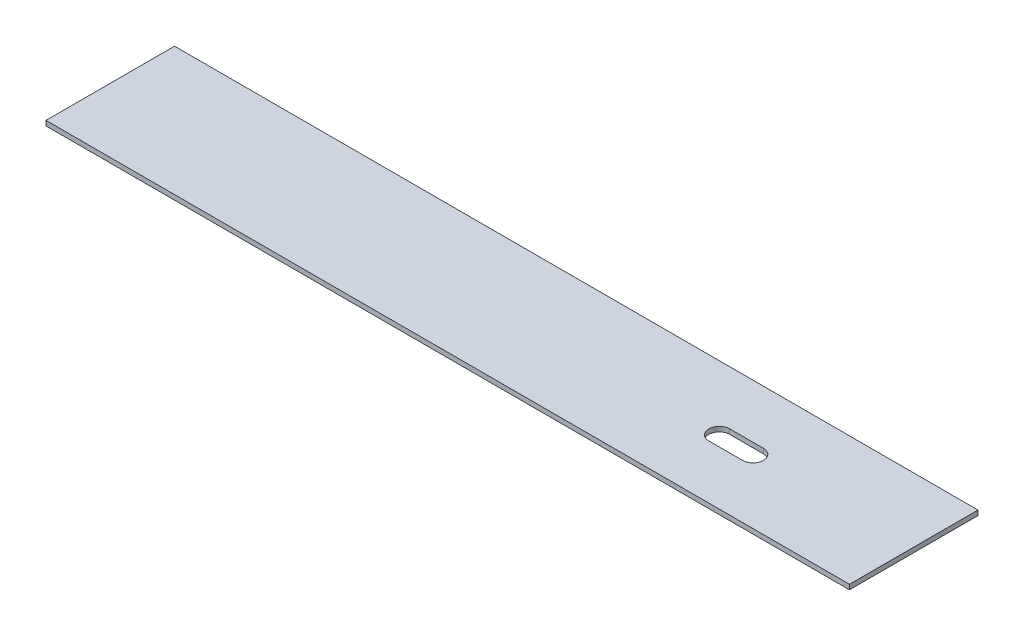
SolidWorks part; units mm, degrees
material "有机玻璃 (TM) GS 丙烯酸铸钣"
ref_plane "前视基准面" through (0, 0, 0) normal (0, 0, 1) x (1, 0, 0)
ref_plane "上视基准面" through (0, 0, 0) normal (0, 1, 0) x (1, 0, 0)
ref_plane "右视基准面" through (0, 0, 0) normal (1, 0, 0) x (0, 0, -1)
other "Configuration Table"
sketch "草图1" plane through (0, 0, 0) normal (0, 1, 0) x (1, 0, 0)
  line L1 (-250, 40) -> (250, 40)
  line L2 (-250, 40) -> (-250, -40)
  line L3 (-250, -40) -> (250, -40)
  line L4 (250, 40) -> (250, -40)
  line L5 (-250, 40) -> (250, -40) construction
  line L6 (-250, -40) -> (250, 40) construction
  point P0 (0, 0)
  dimension "D1" = 500
  dimension "D2" = 80
extrude "凸台-拉伸1" add sketch "草图1" along normal blind 3
sketch "草图2" plane through (0, 3, 0) normal (0, 1, 0) x (1, 0, 0)
  line L0 (0, 0) -> (-50000, 0) construction
  line L1 (129, 6.5) -> (150, 6.5)
  line L2 (129, -6.5) -> (150, -6.5)
  line L3 (250, -40) -> (250, 40) construction
  arc A0 (129, 6.5) -> (129, -6.5) centre (129, 0) ccw
  arc A1 (150, -6.5) -> (150, 6.5) centre (150, 0) ccw
  point P11 (0, 0)
  dimension "D1" = 13
  dimension "D2" = 13
  dimension "D3" = 21
  dimension "D4" = 100
extrude "切除-拉伸1" cut sketch "草图2" against normal blind 10
